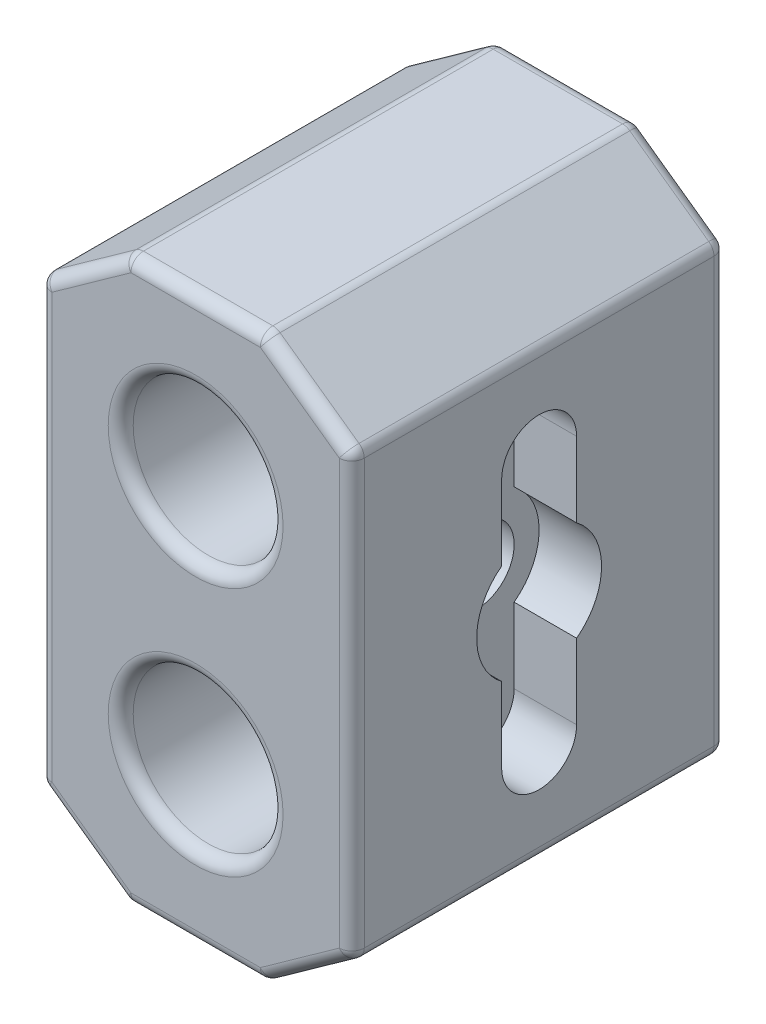
SolidWorks part; units mm, degrees
ref_plane "Front Plane" through (0, 0, 0) normal (0, 0, 1) x (1, 0, 0)
ref_plane "Top Plane" through (0, 0, 0) normal (0, 1, 0) x (1, 0, 0)
ref_plane "Right Plane" through (0, 0, 0) normal (1, 0, 0) x (0, 0, -1)
sketch "Sketch1" plane through (0, 0, 0) normal (0, 0, 1) x (1, 0, 0)
  line L1 (0, 0) -> (25, 0)
  line L2 (0, 0) -> (0, 45)
  line L3 (0, 45) -> (25, 45)
  line L4 (25, 0) -> (25, 45)
  dimension "D1" = 25
  dimension "D2" = 45
extrude "Boss-Extrude1" add sketch "Sketch1" along normal blind 30
sketch "Sketch2" plane through (0, 0, 30) normal (0, 0, 1) x (1, 0, 0)
  line L0 (12.5, 0) -> (12.5, 45) construction
  line L1 (0, 0) -> (25, 0) construction
  line L2 (25, 45) -> (0, 45) construction
  line L3 (0, 45) -> (0, 0) construction
  line L4 (-2.8862, 22.5) -> (28.9951, 22.5) construction
  circle A0 centre (12.5, 12.5) radius 6
  circle A1 centre (12.5, 32.5) radius 6
  dimension "D3" = 12
  dimension "D4" = 12
  dimension "D1" = 10
  dimension "D2" = 10
  dimension "D5" = 22.5
  dimension "D6" = 12.5
extrude "Cut-Extrude1" cut sketch "Sketch2" against normal up to next
sketch "Sketch3" plane through (25, 0, 0) normal (1, 0, 0) x (0, 0, -1)
  line L0 (-15, 0) -> (-15, 12.5) construction
  line L1 (-30, 0) -> (0, 0) construction
  line L2 (-30, 45) -> (0, 45) construction
  line L4 (-12, 32.5) -> (-12, 26.5)
  line L5 (-18, 32.5) -> (-18, 26.5)
  line L6 (-30, 22.5) -> (-20, 22.5) construction
  line L7 (-30, 0) -> (-30, 45) construction
  line L8 (0, 0) -> (0, 45) construction
  line L9 (-18, 18.5) -> (-18, 12.5)
  line L12 (-15, 32.5) -> (-15, 45) construction
  line L13 (-12, 18.5) -> (-12, 12.5)
  line L14 (-10, 22.5) -> (0, 22.5) construction
  arc A0 (-12, 32.5) -> (-18, 32.5) centre (-15, 32.5) ccw
  arc A1 (-18, 12.5) -> (-12, 12.5) centre (-15, 12.5) ccw
  arc A2 (-18, 26.5) -> (-18, 18.5) centre (-15, 22.5) ccw
  arc A3 (-12, 18.5) -> (-12, 26.5) centre (-15, 22.5) ccw
  point P8 (-15, 22.5)
  dimension "D2" = 10
  dimension "D4" = 3
  dimension "D9" = 3
  dimension "D1" = 20
  dimension "D3" = 0
  dimension "D5" = 15
  dimension "D6" = 10
  dimension "D7" = 3
  dimension "D8" = 3
  dimension "D10" = 3
extrude "Cut-Extrude10" cut sketch "Sketch3" against normal blind 5
sketch "Sketch8" plane through (0, 0, 30) normal (0, 0, 1) x (1, 0, 0)
  line L0 (7, 45) -> (0, 40)
  line L1 (0, 45) -> (7, 45)
  line L2 (0, 45) -> (0, 40)
  line L3 (0, 0) -> (7, 0)
  line L4 (25, 45) -> (25, 40)
  line L5 (0, 5) -> (7, 0)
  line L6 (25, 5) -> (18, 0)
  line L7 (18, 45) -> (25, 40)
  line L8 (0, 5) -> (0, 0)
  line L9 (18, 45) -> (25, 45)
  line L10 (25, 5) -> (25, 0)
  line L11 (18, 0) -> (25, 0)
  dimension "D1" = 5
  dimension "D2" = 5
  dimension "D3" = 5
  dimension "D4" = 5
  dimension "D5" = 7
  dimension "D6" = 7
  dimension "D7" = 7
  dimension "D8" = 7
extrude "Cut-Extrude11" cut sketch "Sketch8" against normal through all both and the other way through all
sketch "Sketch9" plane through (0, 0, 0) normal (-1, 0, 0) x (0, 0, 1)
  line L0 (0, 40) -> (0, 5) construction
  line L2 (0, 40) -> (30, 40) construction
  circle A0 centre (15, 22.5) radius 3
  dimension "D1" = 6
  dimension "D2" = 15
  dimension "D3" = 17.5
extrude "Cut-Extrude23" cut sketch "Sketch9" along normal blind 2 from surface at -20 starting at face at (20, 22.5, 15)
fillet "Fillet1" radius 1 28 edges at (7, 45, 15) (12.5, 45, 0) (18, 45, 15) (12.5, 45, 30) (0, 40, 15) (25, 40, 15) (25, 5, 15) (18, 0, 15) (7, 0, 15) (0, 5, 15) (21.5, 2.5, 0) (12.5, 0, 0) (3.5, 2.5, 0) (21.5, 42.5, 0) (3.5, 42.5, 0) (25, 22.5, 0) (0, 22.5, 0) (6.5, 12.5, 0) (6.5, 32.5, 0) (21.5, 2.5, 30) (12.5, 0, 30) (3.5, 2.5, 30) (0, 22.5, 30) (3.5, 42.5, 30) (21.5, 42.5, 30) (25, 22.5, 30) (18.5, 12.5, 30) (18.5, 32.5, 30)
sketch "Sketch10" plane through (25, 0, 0) normal (1, 0, 0) x (0, 0, -1)
  point P0 (-15, 22.5)
